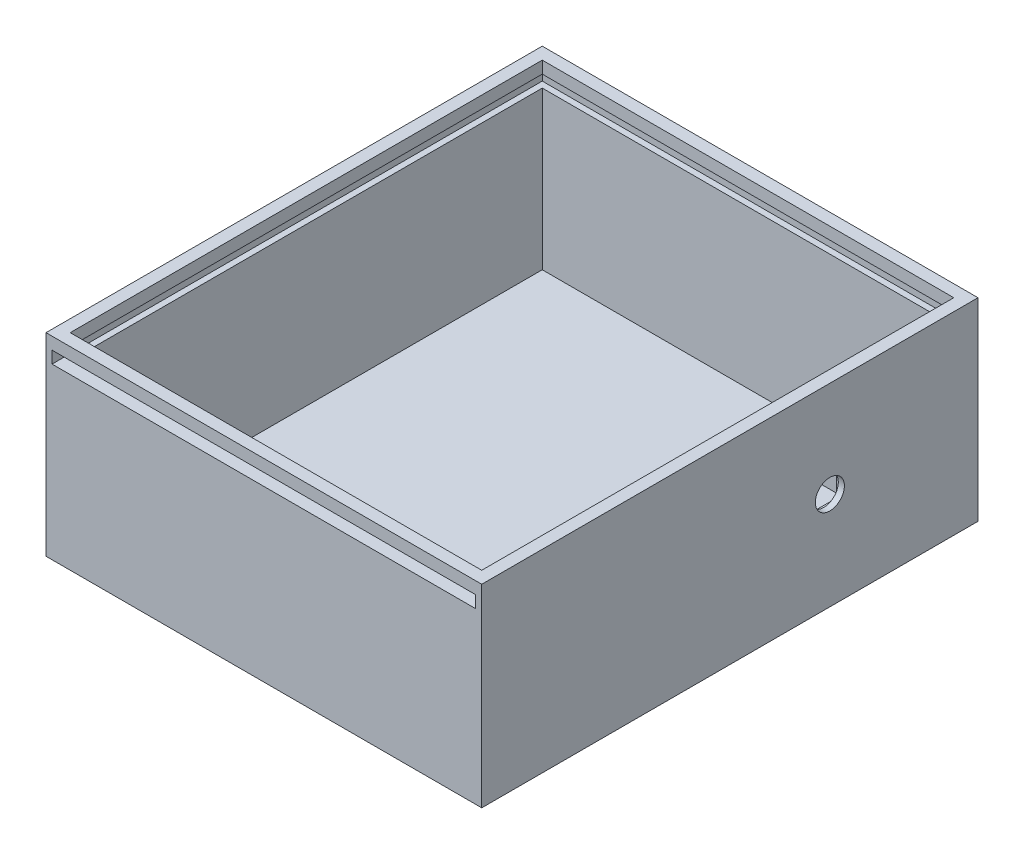
SolidWorks part; units mm, degrees
ref_plane "Front Plane" through (0, 0, 0) normal (0, 0, 1) x (1, 0, 0)
ref_plane "Top Plane" through (0, 0, 0) normal (0, 1, 0) x (1, 0, 0)
ref_plane "Right Plane" through (0, 0, 0) normal (1, 0, 0) x (0, 0, -1)
sketch "Sketch1" plane through (0, 0, 0) normal (0, 1, 0) x (1, 0, 0)
  line L1 (-57.15, 65.0875) -> (57.15, 65.0875)
  line L2 (-57.15, 65.0875) -> (-57.15, -65.0875)
  line L3 (-57.15, -65.0875) -> (57.15, -65.0875)
  line L4 (57.15, 65.0875) -> (57.15, -65.0875)
  line L5 (-57.15, 65.0875) -> (57.15, -65.0875) construction
  line L6 (-57.15, -65.0875) -> (57.15, 65.0875) construction
  point P0 (0, 0)
extrude "Boss-Extrude1" add sketch "Sketch1" along normal blind 50.8
shell "Shell1" thickness 3.175
sketch "Sketch2" plane through (57.15, 0, 0) normal (1, 0, 0) x (0, 0, -1)
  circle A0 centre (26.2255, 25.6032) radius 3.81
extrude "Cut-Extrude1" cut sketch "Sketch2" against normal blind 2.54
sketch "Sketch5" plane through (57.15, 0, 0) normal (1, 0, 0) x (0, 0, -1)
  line L1 (31.1692, 30.5378) -> (21.2818, 30.5378)
  line L2 (31.1692, 30.5378) -> (31.1692, 20.6686)
  line L3 (31.1692, 20.6686) -> (21.2818, 20.6686)
  line L4 (21.2818, 30.5378) -> (21.2818, 20.6686)
  line L5 (31.1692, 30.5378) -> (21.2818, 20.6686) construction
  line L6 (31.1692, 20.6686) -> (21.2818, 30.5378) construction
  circle A0 centre (26.2255, 25.6032) radius 3.429 construction
  point P0 (26.2255, 25.6032)
  dimension "D1" = 0
extrude "Cut-Extrude3" cut sketch "Sketch5" along normal blind 1.5875 from surface at -3.175 starting at face at (53.975, 26.9875, 0)
sketch "Sketch6" plane through (0, 3.175, 0) normal (0, 1, 0) x (1, 0, 0)
  line L0 (53.975, -61.9125) -> (53.975, 61.9125) construction
  line L1 (53.975, -23.0613) -> (24.6507, -23.0613)
  line L2 (53.975, -23.0613) -> (53.975, -29.4113)
  line L3 (53.975, -29.4113) -> (24.6507, -29.4113)
  line L4 (24.6507, -23.0613) -> (24.6507, -29.4113)
  line L5 (24.6507, -46.2534) -> (24.6507, 59.3725) construction
  line L7 (53.975, 56.109) -> (24.6507, 56.109)
  line L8 (53.975, 56.109) -> (53.975, 49.759)
  line L9 (53.975, 49.759) -> (24.6507, 49.759)
  line L10 (24.6507, 56.109) -> (24.6507, 49.759)
extrude "Boss-Extrude2" add sketch "Sketch6" along normal blind 6.35
sketch "Sketch7" plane through (0, 50.8, 0) normal (0, 1, 0) x (1, 0, 0)
  line L0 (-57.15, 0) -> (-55.5625, 0) construction
  line L1 (-57.15, 65.0875) -> (-57.15, -65.0875) construction
  line L2 (57.15, 0) -> (55.5625, 0) construction
  line L3 (57.15, -65.0875) -> (57.15, 65.0875) construction
  line L4 (0, 65.0875) -> (0, 63.5) construction
  line L5 (57.15, 65.0875) -> (-57.15, 65.0875) construction
  line L6 (0, 63.5) -> (-55.5625, 63.5)
  line L7 (-55.5625, 63.5) -> (-55.5625, -65.0875)
  line L8 (-57.15, -65.0875) -> (57.15, -65.0875) construction
  line L9 (-55.5625, -65.0875) -> (55.5625, -65.0875)
  line L10 (55.5625, -65.0875) -> (55.5625, 63.5)
  line L11 (55.5625, 63.5) -> (0, 63.5)
extrude "Cut-Extrude4" cut sketch "Sketch7" against normal blind 3.175 from offset 3.175 offset against normal yes
sketch "Sketch8" plane through (0, 0, 0) normal (0, -1, 0) x (-1, 0, 0)
  line L0 (12.7, -65.0875) -> (12.7, 65.0875) construction
  line L1 (-57.15, 65.0875) -> (57.15, 65.0875) construction
  line L2 (57.15, -65.0875) -> (-57.15, -65.0875) construction
  text T0 "PARKY" font "Century Gothic" height in points 72
extrude "Cut-Extrude5" cut sketch "Sketch8" against normal blind 0.508
